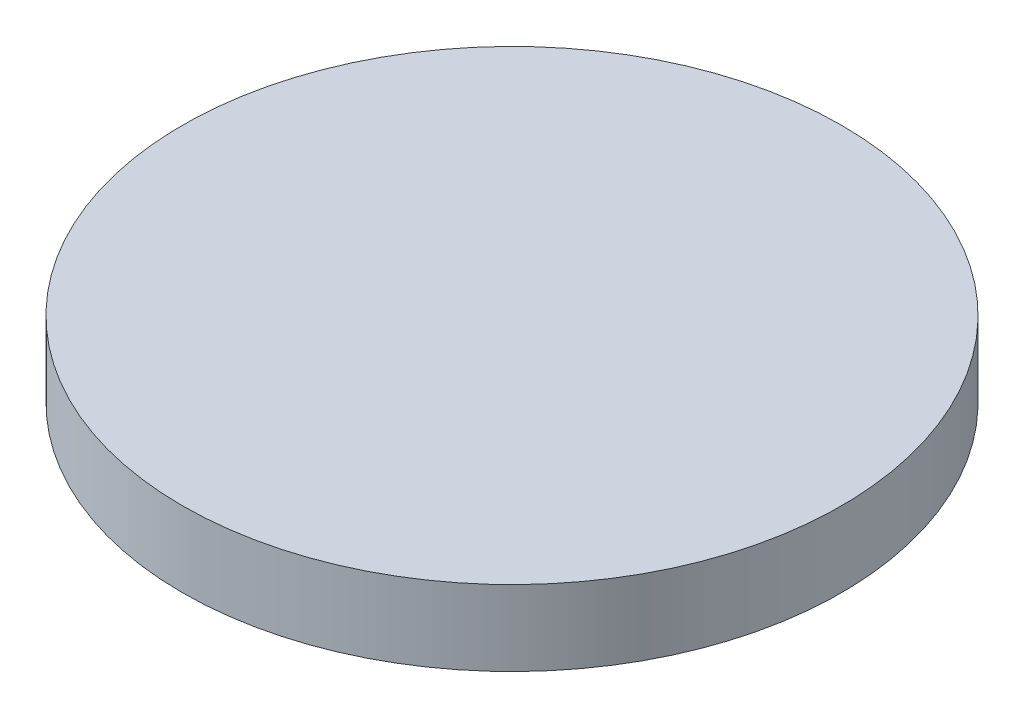
SolidWorks part; units mm, degrees
ref_plane "Front Plane" through (0, 0, 0) normal (0, 0, 1) x (1, 0, 0)
ref_plane "Top Plane" through (0, 0, 0) normal (0, 1, 0) x (1, 0, 0)
ref_plane "Right Plane" through (0, 0, 0) normal (1, 0, 0) x (0, 0, -1)
sketch "Sketch1" plane through (0, 0, 0) normal (0, 1, 0) x (1, 0, 0)
  circle A0 centre (0, 0) radius 35
  dimension "D1" = 70
extrude "Boss-Extrude1" add sketch "Sketch1" along normal blind 8
